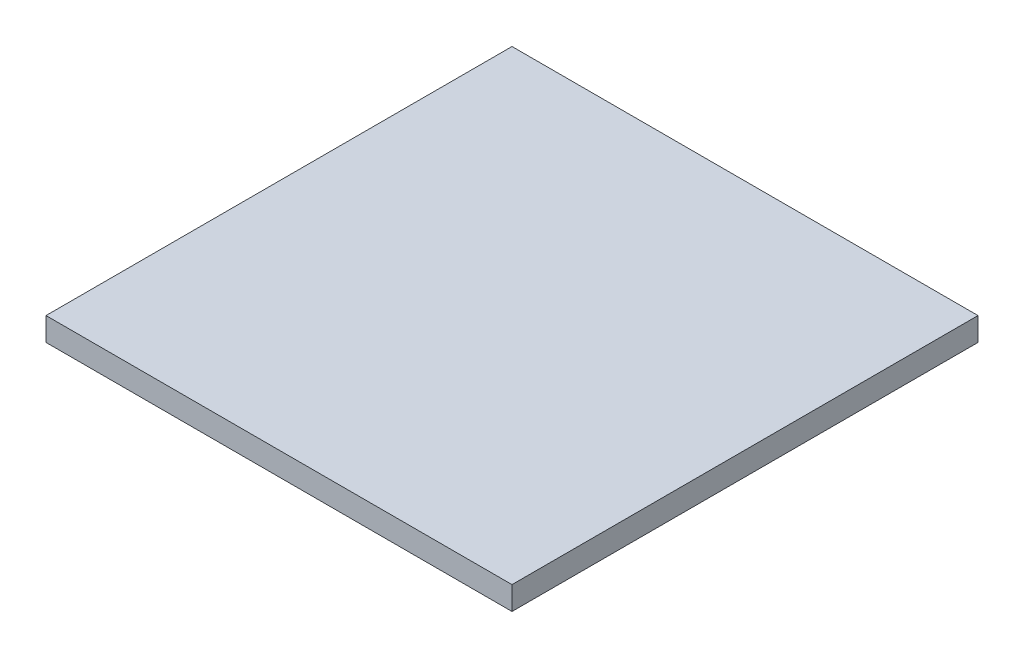
SolidWorks part; units mm, degrees
ref_plane "Front Plane" through (0, 0, 0) normal (0, 0, 1) x (1, 0, 0)
ref_plane "Top Plane" through (0, 0, 0) normal (0, 1, 0) x (1, 0, 0)
ref_plane "Right Plane" through (0, 0, 0) normal (1, 0, 0) x (0, 0, -1)
sketch "Sketch2" plane through (0, 0, 0) normal (0, 1, 0) x (1, 0, 0)
  line L1 (-200, 200) -> (200, 200)
  line L2 (-200, 200) -> (-200, -200)
  line L3 (-200, -200) -> (200, -200)
  line L4 (200, 200) -> (200, -200)
  line L5 (-200, 200) -> (200, -200) construction
  line L6 (-200, -200) -> (200, 200) construction
  point P0 (0, 0)
  dimension "D1" = 400
  dimension "D2" = 400
extrude "Boss-Extrude1" add sketch "Sketch2" along normal blind 20
sketch "Sketch3" plane through (0, 20, 0) normal (0, 1, 0) x (1, 0, 0)
